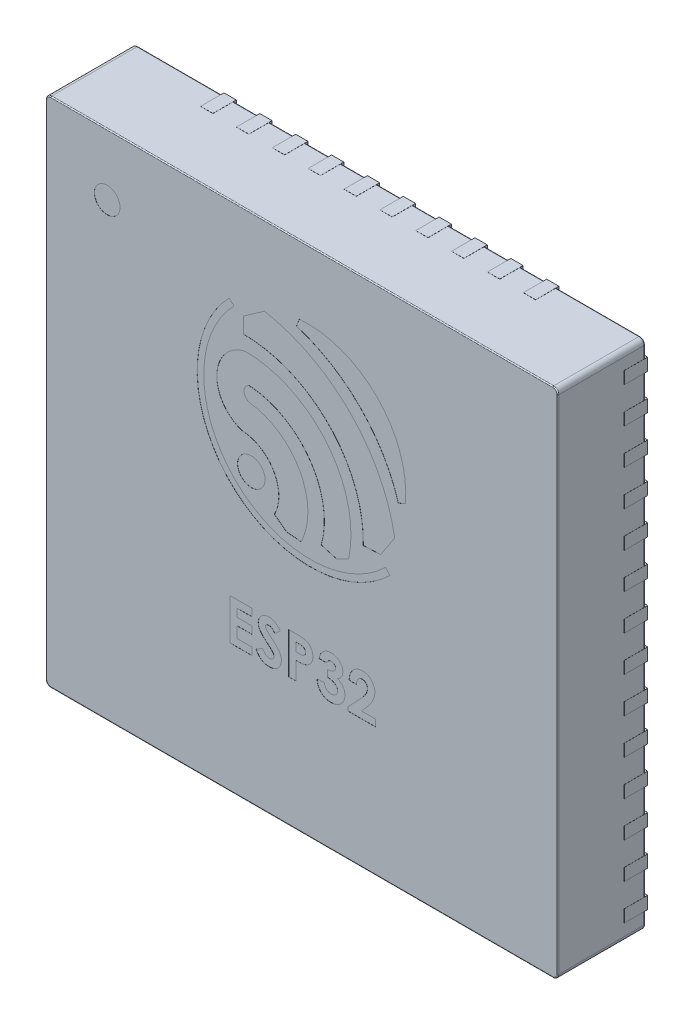
SolidWorks part; units mm, degrees
other "ESP32-SoC-5x5" parameters "D5"=0.3678, "D12"=0.0228, "D1"=3.1308, "D2"=3.0402, "D3"=0.4115, "D4"=0.3, "D6"=0.3296, "D7"=0.2637, "D8"=0.9806, "D10"=0.35, "D11"=0.25, "D13"=0.1644, "D9"=5
ref_plane "Front Plane" through (0, 0, 0) normal (0, 0, 1) x (1, 0, 0)
ref_plane "Top Plane" through (0, 0, 0) normal (0, 1, 0) x (1, 0, 0)
ref_plane "Right Plane" through (0, 0, 0) normal (1, 0, 0) x (0, 0, -1)
sketch "Sketch1" plane through (0, 0, 0) normal (0, 1, 0) x (1, 0, 0)
  line L1 (-2.5, -2.5) -> (2.5, -2.5)
  line L2 (-2.5, -2.5) -> (-2.5, 2.5)
  line L3 (-2.5, 2.5) -> (2.5, 2.5)
  line L4 (2.5, -2.5) -> (2.5, 2.5)
  line L5 (-2.5, -2.5) -> (2.5, 2.5) construction
  line L6 (-2.5, 2.5) -> (2.5, -2.5) construction
  point P0 (0, 0)
  dimension "D1" = 5
  dimension "D2" = 5
extrude "Boss-Extrude1" add sketch "Sketch1" along normal blind 0.85
fillet "Fillet1" radius 0.05 4 edges at (2.5, 0.425, -2.5) (2.5, 0.425, 2.5) (-2.5, 0.425, 2.5) (-2.5, 0.425, -2.5)
fillet "Fillet2" radius 0.01 16 edges at (2.4854, 0.85, 2.4854) (0, 0.85, 2.5) (-2.4854, 0.85, 2.4854) (-2.5, 0.85, 0) (-2.4854, 0.85, -2.4854) (0, 0.85, -2.5) (2.4854, 0.85, -2.4854) (2.5, 0.85, 0) (2.5, 0, 0) (2.4854, 0, -2.4854) (0, 0, -2.5) (2.4854, 0, 2.4854) (0, 0, 2.5) (-2.4854, 0, 2.4854) (-2.5, 0, 0) (-2.4854, 0, -2.4854)
sketch "Sketch2" plane through (0, 0, 0) normal (0, -1, 0) x (1, 0, 0)
  line L0 (1.5, 1.85) -> (1.85, 1.5)
  line L1 (-1.75, -1.85) -> (1.75, -1.85)
  line L2 (-1.85, -1.75) -> (-1.85, 1.75)
  line L3 (-1.75, 1.85) -> (1.5, 1.85)
  line L4 (1.85, -1.75) -> (1.85, 1.5)
  line L5 (-1.8207, -1.8207) -> (1.85, 1.85) construction
  line L6 (-1.8207, 1.8207) -> (1.8207, -1.8207) construction
  line L7 (1.5, 1.85) -> (1.85, 1.85) construction
  line L8 (1.85, 1.5) -> (1.85, 1.85) construction
  line L9 (-1.85, 1.85) -> (-1.75, 1.85) construction
  line L10 (-1.85, 1.85) -> (-1.8207, 1.8207) construction
  line L11 (-1.85, 1.75) -> (-1.85, 1.85) construction
  line L12 (-1.85, -1.85) -> (-1.85, -1.75) construction
  line L13 (-1.85, -1.85) -> (-1.8207, -1.8207) construction
  line L14 (-1.85, -1.85) -> (-1.75, -1.85) construction
  line L15 (1.85, -1.85) -> (1.85, -1.75) construction
  line L16 (1.8207, -1.8207) -> (1.85, -1.85) construction
  line L17 (1.75, -1.85) -> (1.85, -1.85) construction
  line L18 (0, -1000) -> (0, 49000) construction
  line L23 (-0.235, 2.501) -> (-0.115, 2.501)
  line L24 (-0.235, 2.501) -> (-0.235, 2.151)
  line L25 (-0.235, 2.151) -> (-0.115, 2.151)
  line L26 (-0.115, 2.501) -> (-0.115, 2.151)
  line L27 (-0.235, 2.501) -> (-0.115, 2.151) construction
  line L28 (-0.235, 2.151) -> (-0.115, 2.501) construction
  line L30 (-0.585, 2.501) -> (-0.585, 2.151)
  line L31 (-0.585, 2.501) -> (-0.465, 2.501)
  line L32 (-0.465, 2.501) -> (-0.465, 2.151)
  line L33 (-0.585, 2.151) -> (-0.465, 2.151)
  line L34 (-0.585, 2.151) -> (-0.465, 2.501) construction
  line L35 (-0.585, 2.501) -> (-0.465, 2.151) construction
  line L36 (-0.935, 2.501) -> (-0.935, 2.151)
  line L37 (-0.935, 2.501) -> (-0.815, 2.501)
  line L38 (-0.815, 2.501) -> (-0.815, 2.151)
  line L39 (-0.935, 2.151) -> (-0.815, 2.151)
  line L40 (-0.935, 2.151) -> (-0.815, 2.501) construction
  line L41 (-0.935, 2.501) -> (-0.815, 2.151) construction
  line L42 (-1.285, 2.501) -> (-1.285, 2.151)
  line L43 (-1.285, 2.501) -> (-1.165, 2.501)
  line L44 (-1.165, 2.501) -> (-1.165, 2.151)
  line L45 (-1.285, 2.151) -> (-1.165, 2.151)
  line L46 (-1.285, 2.151) -> (-1.165, 2.501) construction
  line L47 (-1.285, 2.501) -> (-1.165, 2.151) construction
  line L48 (-0.235, 2.501) -> (-0.585, 2.501) construction
  line L49 (-1.635, 2.501) -> (-1.635, 2.151)
  line L66 (-1.635, 2.501) -> (-1.515, 2.501)
  line L162 (-1000, 0) -> (49000, 0) construction
  line L163 (-2.5, 2.5) -> (2.5, 2.5) construction
  line L164 (-1.515, 2.501) -> (-1.515, 2.151)
  line L165 (-1.635, 2.151) -> (-1.515, 2.151)
  line L166 (-1.635, 2.151) -> (-1.515, 2.501) construction
  line L167 (-1.635, 2.501) -> (-1.515, 2.151) construction
  line L168 (1.635, 2.501) -> (1.515, 2.151) construction
  line L179 (1.635, 2.151) -> (1.515, 2.501) construction
  line L180 (0.235, 2.501) -> (0.585, 2.501) construction
  line L181 (1.285, 2.501) -> (1.165, 2.151) construction
  line L182 (1.285, 2.151) -> (1.165, 2.501) construction
  line L183 (0.935, 2.501) -> (0.815, 2.151) construction
  line L184 (0.935, 2.151) -> (0.815, 2.501) construction
  line L185 (0.585, 2.501) -> (0.465, 2.151) construction
  line L186 (0.585, 2.151) -> (0.465, 2.501) construction
  line L187 (0.235, 2.151) -> (0.115, 2.501) construction
  line L188 (0.235, 2.501) -> (0.115, 2.151) construction
  line L189 (1.635, 2.151) -> (1.515, 2.151)
  line L190 (1.515, 2.501) -> (1.515, 2.151)
  line L191 (1.635, 2.501) -> (1.515, 2.501)
  line L192 (1.635, 2.501) -> (1.635, 2.151)
  line L193 (1.285, 2.151) -> (1.165, 2.151)
  line L194 (1.165, 2.501) -> (1.165, 2.151)
  line L195 (1.285, 2.501) -> (1.165, 2.501)
  line L196 (1.285, 2.501) -> (1.285, 2.151)
  line L197 (0.935, 2.151) -> (0.815, 2.151)
  line L198 (0.815, 2.501) -> (0.815, 2.151)
  line L199 (0.935, 2.501) -> (0.815, 2.501)
  line L200 (0.935, 2.501) -> (0.935, 2.151)
  line L201 (0.585, 2.151) -> (0.465, 2.151)
  line L202 (0.465, 2.501) -> (0.465, 2.151)
  line L203 (0.585, 2.501) -> (0.465, 2.501)
  line L204 (0.585, 2.501) -> (0.585, 2.151)
  line L205 (0.115, 2.501) -> (0.115, 2.151)
  line L206 (0.235, 2.151) -> (0.115, 2.151)
  line L207 (0.235, 2.501) -> (0.235, 2.151)
  line L208 (0.235, 2.501) -> (0.115, 2.501)
  line L209 (0.235, -2.501) -> (0.115, -2.151) construction
  line L210 (0.235, -2.151) -> (0.115, -2.501) construction
  line L211 (0.585, -2.151) -> (0.465, -2.501) construction
  line L212 (0.585, -2.501) -> (0.465, -2.151) construction
  line L213 (0.935, -2.151) -> (0.815, -2.501) construction
  line L214 (0.935, -2.501) -> (0.815, -2.151) construction
  line L215 (1.285, -2.151) -> (1.165, -2.501) construction
  line L216 (1.285, -2.501) -> (1.165, -2.151) construction
  line L217 (0.235, -2.501) -> (0.585, -2.501) construction
  line L218 (1.635, -2.151) -> (1.515, -2.501) construction
  line L219 (1.635, -2.501) -> (1.515, -2.151) construction
  line L220 (-1.635, -2.501) -> (-1.515, -2.151) construction
  line L221 (-1.635, -2.151) -> (-1.515, -2.501) construction
  line L222 (-0.235, -2.501) -> (-0.585, -2.501) construction
  line L223 (-1.285, -2.501) -> (-1.165, -2.151) construction
  line L224 (-1.285, -2.151) -> (-1.165, -2.501) construction
  line L225 (-0.935, -2.501) -> (-0.815, -2.151) construction
  line L226 (-0.935, -2.151) -> (-0.815, -2.501) construction
  line L227 (-0.585, -2.501) -> (-0.465, -2.151) construction
  line L228 (-0.585, -2.151) -> (-0.465, -2.501) construction
  line L229 (-0.235, -2.151) -> (-0.115, -2.501) construction
  line L230 (-0.235, -2.501) -> (-0.115, -2.151) construction
  line L231 (0.235, -2.501) -> (0.115, -2.501)
  line L232 (0.235, -2.501) -> (0.235, -2.151)
  line L233 (0.235, -2.151) -> (0.115, -2.151)
  line L234 (0.115, -2.501) -> (0.115, -2.151)
  line L235 (0.585, -2.501) -> (0.585, -2.151)
  line L236 (0.585, -2.501) -> (0.465, -2.501)
  line L237 (0.465, -2.501) -> (0.465, -2.151)
  line L238 (0.585, -2.151) -> (0.465, -2.151)
  line L239 (0.935, -2.501) -> (0.935, -2.151)
  line L240 (0.935, -2.501) -> (0.815, -2.501)
  line L241 (0.815, -2.501) -> (0.815, -2.151)
  line L242 (0.935, -2.151) -> (0.815, -2.151)
  line L243 (1.285, -2.501) -> (1.285, -2.151)
  line L244 (1.285, -2.501) -> (1.165, -2.501)
  line L245 (1.165, -2.501) -> (1.165, -2.151)
  line L246 (1.285, -2.151) -> (1.165, -2.151)
  line L247 (1.635, -2.501) -> (1.635, -2.151)
  line L248 (1.635, -2.501) -> (1.515, -2.501)
  line L249 (1.515, -2.501) -> (1.515, -2.151)
  line L250 (1.635, -2.151) -> (1.515, -2.151)
  line L251 (-1.635, -2.151) -> (-1.515, -2.151)
  line L252 (-1.515, -2.501) -> (-1.515, -2.151)
  line L253 (-1.635, -2.501) -> (-1.515, -2.501)
  line L254 (-1.635, -2.501) -> (-1.635, -2.151)
  line L255 (-1.285, -2.151) -> (-1.165, -2.151)
  line L256 (-1.165, -2.501) -> (-1.165, -2.151)
  line L257 (-1.285, -2.501) -> (-1.165, -2.501)
  line L258 (-1.285, -2.501) -> (-1.285, -2.151)
  line L259 (-0.935, -2.151) -> (-0.815, -2.151)
  line L260 (-0.815, -2.501) -> (-0.815, -2.151)
  line L261 (-0.935, -2.501) -> (-0.815, -2.501)
  line L262 (-0.935, -2.501) -> (-0.935, -2.151)
  line L263 (-0.585, -2.151) -> (-0.465, -2.151)
  line L264 (-0.465, -2.501) -> (-0.465, -2.151)
  line L265 (-0.585, -2.501) -> (-0.465, -2.501)
  line L266 (-0.585, -2.501) -> (-0.585, -2.151)
  line L267 (-0.115, -2.501) -> (-0.115, -2.151)
  line L268 (-0.235, -2.151) -> (-0.115, -2.151)
  line L269 (-0.235, -2.501) -> (-0.235, -2.151)
  line L270 (-0.235, -2.501) -> (-0.115, -2.501)
  line L271 (-2.151, 0.235) -> (-2.151, 0.115)
  line L272 (-2.501, 0.115) -> (-2.151, 0.115)
  line L273 (-2.501, 0.235) -> (-2.501, 0.115)
  line L274 (-2.501, 0.235) -> (-2.151, 0.235)
  line L275 (-2.151, 0.585) -> (-2.151, 0.465)
  line L276 (-2.501, 0.465) -> (-2.151, 0.465)
  line L277 (-2.501, 0.585) -> (-2.501, 0.465)
  line L278 (-2.501, 0.585) -> (-2.151, 0.585)
  line L279 (-2.151, 0.935) -> (-2.151, 0.815)
  line L280 (-2.501, 0.815) -> (-2.151, 0.815)
  line L281 (-2.501, 0.935) -> (-2.501, 0.815)
  line L282 (-2.501, 0.935) -> (-2.151, 0.935)
  line L283 (-2.151, 1.285) -> (-2.151, 1.165)
  line L284 (-2.501, 1.165) -> (-2.151, 1.165)
  line L285 (-2.501, 1.285) -> (-2.501, 1.165)
  line L286 (-2.501, 1.285) -> (-2.151, 1.285)
  line L287 (-2.151, 1.635) -> (-2.151, 1.515)
  line L288 (-2.501, 1.515) -> (-2.151, 1.515)
  line L289 (-2.501, 1.635) -> (-2.501, 1.515)
  line L290 (-2.501, 1.635) -> (-2.151, 1.635)
  line L291 (-2.151, 1.985) -> (-2.151, 1.865)
  line L292 (-2.501, 1.865) -> (-2.151, 1.865)
  line L293 (-2.501, 1.985) -> (-2.501, 1.865)
  line L294 (-2.501, 1.985) -> (-2.151, 1.985)
  line L295 (-2.151, 2.335) -> (-2.151, 2.215)
  line L296 (-2.501, 2.215) -> (-2.151, 2.215)
  line L297 (-2.501, 2.335) -> (-2.501, 2.215)
  line L298 (-2.501, 2.335) -> (-2.151, 2.335)
  line L299 (-2.151, 0.235) -> (-2.151, 0.585) construction
  line L300 (-2.151, -0.235) -> (-2.151, -0.585) construction
  line L301 (-2.501, -2.335) -> (-2.151, -2.335)
  line L302 (-2.501, -2.335) -> (-2.501, -2.215)
  line L303 (-2.501, -2.215) -> (-2.151, -2.215)
  line L304 (-2.151, -2.335) -> (-2.151, -2.215)
  line L305 (-2.501, -1.985) -> (-2.151, -1.985)
  line L306 (-2.501, -1.985) -> (-2.501, -1.865)
  line L307 (-2.501, -1.865) -> (-2.151, -1.865)
  line L308 (-2.151, -1.985) -> (-2.151, -1.865)
  line L309 (-2.501, -1.635) -> (-2.151, -1.635)
  line L310 (-2.501, -1.635) -> (-2.501, -1.515)
  line L311 (-2.501, -1.515) -> (-2.151, -1.515)
  line L312 (-2.151, -1.635) -> (-2.151, -1.515)
  line L313 (-2.501, -1.285) -> (-2.151, -1.285)
  line L314 (-2.501, -1.285) -> (-2.501, -1.165)
  line L315 (-2.501, -1.165) -> (-2.151, -1.165)
  line L316 (-2.151, -1.285) -> (-2.151, -1.165)
  line L317 (-2.501, -0.935) -> (-2.151, -0.935)
  line L318 (-2.501, -0.935) -> (-2.501, -0.815)
  line L319 (-2.501, -0.815) -> (-2.151, -0.815)
  line L320 (-2.151, -0.935) -> (-2.151, -0.815)
  line L321 (-2.501, -0.585) -> (-2.151, -0.585)
  line L322 (-2.501, -0.585) -> (-2.501, -0.465)
  line L323 (-2.501, -0.465) -> (-2.151, -0.465)
  line L324 (-2.151, -0.585) -> (-2.151, -0.465)
  line L325 (-2.501, -0.235) -> (-2.151, -0.235)
  line L326 (-2.501, -0.235) -> (-2.501, -0.115)
  line L327 (-2.501, -0.115) -> (-2.151, -0.115)
  line L328 (-2.151, -0.235) -> (-2.151, -0.115)
  line L329 (2.151, -0.235) -> (2.151, -0.585) construction
  line L330 (2.151, 0.235) -> (2.151, 0.585) construction
  line L331 (2.151, -0.235) -> (2.151, -0.115)
  line L332 (2.501, -0.115) -> (2.151, -0.115)
  line L333 (2.501, -0.235) -> (2.501, -0.115)
  line L334 (2.501, -0.235) -> (2.151, -0.235)
  line L335 (2.151, -0.585) -> (2.151, -0.465)
  line L336 (2.501, -0.465) -> (2.151, -0.465)
  line L337 (2.501, -0.585) -> (2.501, -0.465)
  line L338 (2.501, -0.585) -> (2.151, -0.585)
  line L339 (2.151, -0.935) -> (2.151, -0.815)
  line L340 (2.501, -0.815) -> (2.151, -0.815)
  line L341 (2.501, -0.935) -> (2.501, -0.815)
  line L342 (2.501, -0.935) -> (2.151, -0.935)
  line L343 (2.151, -1.285) -> (2.151, -1.165)
  line L344 (2.501, -1.165) -> (2.151, -1.165)
  line L345 (2.501, -1.285) -> (2.501, -1.165)
  line L346 (2.501, -1.285) -> (2.151, -1.285)
  line L347 (2.151, -1.635) -> (2.151, -1.515)
  line L348 (2.501, -1.515) -> (2.151, -1.515)
  line L349 (2.501, -1.635) -> (2.501, -1.515)
  line L350 (2.501, -1.635) -> (2.151, -1.635)
  line L351 (2.151, -1.985) -> (2.151, -1.865)
  line L352 (2.501, -1.865) -> (2.151, -1.865)
  line L353 (2.501, -1.985) -> (2.501, -1.865)
  line L354 (2.501, -1.985) -> (2.151, -1.985)
  line L355 (2.151, -2.335) -> (2.151, -2.215)
  line L356 (2.501, -2.215) -> (2.151, -2.215)
  line L357 (2.501, -2.335) -> (2.501, -2.215)
  line L358 (2.501, -2.335) -> (2.151, -2.335)
  line L359 (2.501, 2.335) -> (2.151, 2.335)
  line L360 (2.501, 2.335) -> (2.501, 2.215)
  line L361 (2.501, 2.215) -> (2.151, 2.215)
  line L362 (2.151, 2.335) -> (2.151, 2.215)
  line L363 (2.501, 1.985) -> (2.151, 1.985)
  line L364 (2.501, 1.985) -> (2.501, 1.865)
  line L365 (2.501, 1.865) -> (2.151, 1.865)
  line L366 (2.151, 1.985) -> (2.151, 1.865)
  line L367 (2.501, 1.635) -> (2.151, 1.635)
  line L368 (2.501, 1.635) -> (2.501, 1.515)
  line L369 (2.501, 1.515) -> (2.151, 1.515)
  line L370 (2.151, 1.635) -> (2.151, 1.515)
  line L371 (2.501, 1.285) -> (2.151, 1.285)
  line L372 (2.501, 1.285) -> (2.501, 1.165)
  line L373 (2.501, 1.165) -> (2.151, 1.165)
  line L374 (2.151, 1.285) -> (2.151, 1.165)
  line L375 (2.501, 0.935) -> (2.151, 0.935)
  line L376 (2.501, 0.935) -> (2.501, 0.815)
  line L377 (2.501, 0.815) -> (2.151, 0.815)
  line L378 (2.151, 0.935) -> (2.151, 0.815)
  line L379 (2.501, 0.585) -> (2.151, 0.585)
  line L380 (2.501, 0.585) -> (2.501, 0.465)
  line L381 (2.501, 0.465) -> (2.151, 0.465)
  line L382 (2.151, 0.585) -> (2.151, 0.465)
  line L383 (2.501, 0.235) -> (2.151, 0.235)
  line L384 (2.501, 0.235) -> (2.501, 0.115)
  line L385 (2.501, 0.115) -> (2.151, 0.115)
  line L386 (2.151, 0.235) -> (2.151, 0.115)
  arc A0 (-1.75, 1.85) -> (-1.85, 1.75) centre (-1.75, 1.75) ccw
  arc A1 (-1.85, -1.75) -> (-1.75, -1.85) centre (-1.75, -1.75) ccw
  arc A2 (1.75, -1.85) -> (1.85, -1.75) centre (1.75, -1.75) ccw
  point P0 (0, 0)
  point P12 (-0.175, 2.326)
  point P70 (0.175, 2.326)
  point P111 (0.175, -2.326)
  point P112 (-0.175, -2.326)
  dimension "D5" = 0.2
  dimension "D1" = 3.7
  dimension "D2" = 3.7
  dimension "D4" = 45
  dimension "D6" = 0.35
  dimension "D7" = 0.12
  dimension "D8" = 0.175
  dimension "D11" = 0.001
  dimension "D13" = 0.35
  dimension "D3" = 0.35
  dimension "D12" = 7
extrude "Boss-Extrude2" add sketch "Sketch2" along normal blind 0.025 and the other way blind 0.203
sketch "Sketch3" plane through (0, 0.85, 0) normal (0, 1, 0) x (1, 0, 0)
  line L7 (-2.5, 1.245) -> (2.5, 1.245) construction
  line L8 (-2.5, 2.5) -> (-2.5, -2.5) construction
  line L9 (-0.9421, -0.7588) -> (-1.0111, -0.7882)
  line L11 (2.5, 2.45) -> (2.5, -2.45) construction
  line L12 (2.45, -2.5) -> (-2.45, -2.5) construction
  line L13 (0.0255, -1.8302) -> (0.0518, -1.7568)
  line L14 (-0.5992, -0.2289) -> (-0.7693, -0.2362)
  line L15 (-0.7693, -0.2362) -> (-0.9068, -0.4461)
  line L16 (0.3651, -1.7276) -> (0.5715, -1.5828)
  line L17 (0.5715, -1.5828) -> (0.5715, -1.4307)
  line L18 (0.6619, -1.6233) -> (0.71, -1.6659)
  line L19 (-0.86, -0.1057) -> (-0.8172, -0.1536)
  line L20 (0.2674, -0.0588) -> (0.149, 0.0307)
  line L21 (0.149, 0.0307) -> (0.0069, 0.0432)
  line L22 (-0.1893, -0.0293) -> (-0.3395, 0.0154)
  line L23 (-0.3395, 0.0154) -> (-0.4566, -0.0432)
  line L24 (0, 0) -> (0, 2.49) construction
  line L25 (2.45, 2.49) -> (-2.45, 2.49) construction
  circle A10 centre (1.9, -1.9) radius 0.125
  arc A11 (-0.9421, -0.7588) -> (0.0518, -1.7568) centre (0.4933, -0.3233) ccw
  arc A12 (-0.9068, -0.4461) -> (0.3651, -1.7276) centre (0.6452, -0.1777) ccw
  arc A13 (0.5542, -1.2949) -> (0.5837, -0.608) centre (0.4738, -0.9474) ccw
  arc A14 (0.71, -1.6659) -> (-0.86, -0.1057) centre (-0.0851, -0.896) ccw
  circle A15 centre (0.4933, -0.3067) radius 0.1343
  arc A16 (-0.1893, -0.0293) -> (0.5112, -1.0234) centre (0.5607, -0.2447) ccw
  arc A17 (0.2674, -0.0588) -> (0.5837, -0.608) centre (0.5998, -0.2331) ccw
  arc A18 (0.0069, 0.0432) -> (0.5138, -0.8823) centre (0.5854, -0.2415) ccw
  arc A19 (-0.4566, -0.0432) -> (0.5542, -1.2949) centre (0.5546, -0.2606) ccw
  arc A20 (0.6619, -1.6233) -> (-0.8172, -0.1536) centre (-0.0851, -0.896) ccw
  arc A21 (-0.5992, -0.2289) -> (0.5715, -1.4307) centre (0.5703, -0.2608) ccw
  arc A22 (0.5138, -0.8823) -> (0.5112, -1.0234) centre (0.4901, -0.9524) cw
  arc A23 (-1.0111, -0.7882) -> (0.0255, -1.8302) centre (-0.0541, -0.8727) ccw
  text T0 "ESP32" font "Century Gothic" height 0.4
  point P0 (0, 1.245)
  point P52 (0, 0)
  dimension "D2" = 0.25
  dimension "D3" = 0.6
  dimension "D4" = 0.6
extrude "Cut-Extrude1" cut sketch "Sketch3" against normal blind 0.001
move or copy body "Body-Move/Copy1" bodies to move or copy 131 copy no rotation origin (0, 0, 0) rotation axis (0, 0.7071, 0.7071) rotation angle 180
move or copy body "Body-Move/Copy2" bodies to move or copy 132 copy no translate (0, 0, 0.025)
equation "\"D8@Sketch2\"=\"D10@Sketch2\"/2"
equation "\"D1@Sketch2\"=\"D2@Sketch2\""
equation "\"D4@Sketch3\"=\"D3@Sketch3\""
